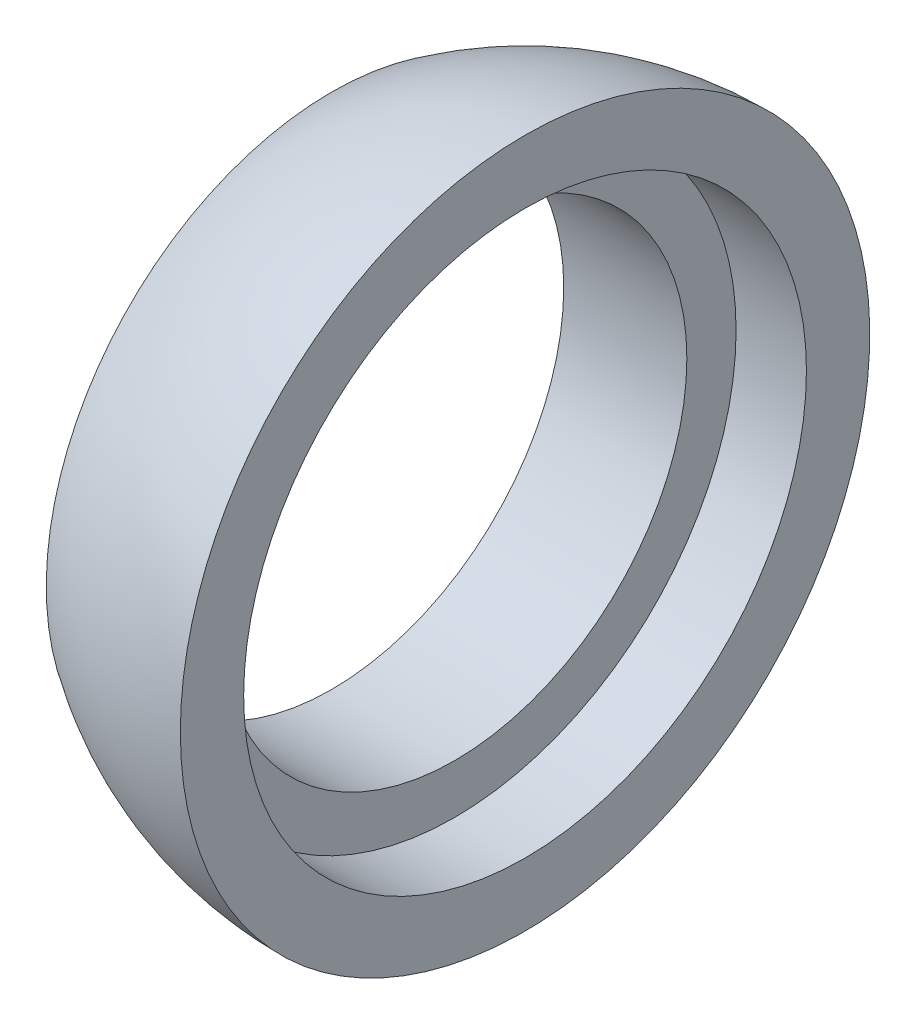
SolidWorks part; units mm, degrees
ref_plane "前视基准面" through (0, 0, 0) normal (0, 0, 1) x (1, 0, 0)
ref_plane "上视基准面" through (0, 0, 0) normal (0, 1, 0) x (1, 0, 0)
ref_plane "右视基准面" through (0, 0, 0) normal (1, 0, 0) x (0, 0, -1)
other "Configuration Table"
sketch "草图1" plane through (0, 0, 0) normal (1, 0, 0) x (0, 0, -1)
  line L0 (0, 9.8) -> (0, -9.8)
  arc A0 (0, 9.8) -> (0, -9.8) centre (0, 0) ccw
  dimension "D1" = 9.8
revolve "旋转1" add sketch "草图1" angle 180 about L0
sketch "草图5" plane through (0, 0, 0) normal (0, 0, 1) x (1, 0, 0)
  line L0 (0, -9.8) -> (0, 9.8) construction
  line L1 (-10.4392, 9.0387) -> (-5.5, 9.0387)
  line L2 (-10.4392, 9.0387) -> (-10.4392, -9.903)
  line L3 (-10.4392, -9.903) -> (-5.5, -9.903)
  line L4 (-5.5, 9.0387) -> (-5.5, -9.903)
  dimension "D1" = 18.9417
  dimension "D2" = 5.5
extrude "切除-拉伸3" cut sketch "草图5" against normal through all and the other way through all
sketch "草图11" plane through (0, 0, 0) normal (1, 0, 0) x (0, 0, -1)
  circle A0 centre (0, 0) radius 6.6
  dimension "D1" = 13.2
extrude "切除-拉伸7" cut sketch "草图11" against normal through all
sketch "草图12" plane through (0, 0, 0) normal (1, 0, 0) x (0, 0, -1)
  circle A0 centre (0, 0) radius 8
  dimension "D1" = 16
extrude "切除-拉伸8" cut sketch "草图12" against normal blind 2
